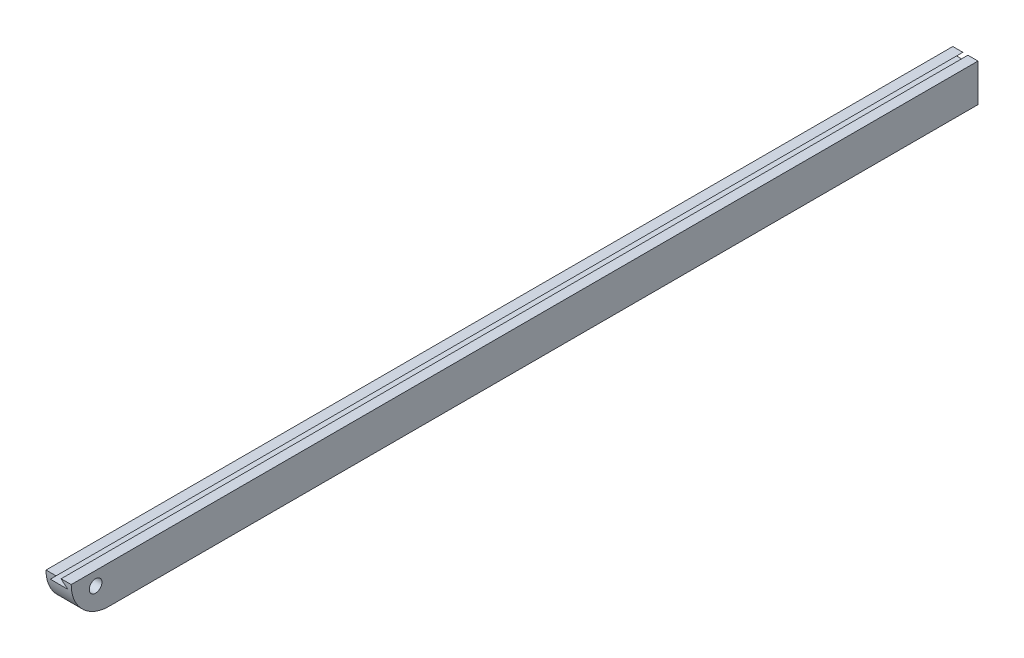
SolidWorks part; units mm, degrees
ref_plane "Front Plane" through (0, 0, 0) normal (0, 0, 1) x (1, 0, 0)
ref_plane "Top Plane" through (0, 0, 0) normal (0, 1, 0) x (1, 0, 0)
ref_plane "Right Plane" through (0, 0, 0) normal (1, 0, 0) x (0, 0, -1)
sketch "Sketch1" plane through (0, 0, 0) normal (0, 0, 1) x (1, 0, 0)
  line L0 (5.08, 0) -> (1.905, -3.175)
  line L1 (0, 0) -> (5.08, 0)
  line L2 (0, 0) -> (0, -19.05)
  line L3 (0, -19.05) -> (12.7, -19.05)
  line L4 (12.7, 0) -> (12.7, -19.05)
  line L5 (1.905, -3.175) -> (10.795, -3.175)
  line L6 (10.795, -3.175) -> (7.62, 0)
  line L7 (7.62, 0) -> (12.7, 0)
  dimension "D1" = 12.7
  dimension "D2" = 19.05
  dimension "D3" = 3.175
  dimension "D4" = 45
  dimension "D5" = 45
  dimension "D6" = 8.89
  dimension "D7" = 1.905
extrude "Boss-Extrude1" add sketch "Sketch1" along normal blind 457.2
sketch "Sketch2" plane through (12.7, 0, 0) normal (1, 0, 0) x (0, 0, -1)
  line L0 (-457.2, 0) -> (0, 0) construction
  line L1 (-457.2, -19.05) -> (-457.2, 0) construction
  line L2 (-457.2, -19.05) -> (0, -19.05) construction
  line L3 (-457.2, 0) -> (-457.2, -19.05)
  line L4 (-457.2, -19.05) -> (-438.15, -19.05)
  arc A0 (-457.2, 0) -> (-438.15, -19.05) centre (-438.15, 0) ccw
extrude "Cut-Extrude1" cut sketch "Sketch2" against normal through all
sketch "Sketch3" plane through (12.7, 0, 0) normal (1, 0, 0) x (0, 0, -1)
  line L0 (-451.6204, -13.4704) -> (-438.15, 0) construction
  circle A0 centre (-444.8852, -6.7352) radius 3.175
  arc A1 (-457.2, 0) -> (-438.15, -19.05) centre (-438.15, 0) ccw construction
  point P8 (-444.8852, -6.7352)
  dimension "D1" = 6.35
extrude "Cut-Extrude2" cut sketch "Sketch3" against normal through all
sketch "Sketch4" plane through (0, 0, 0) normal (0, 0, -1) x (-1, 0, 0)
  line L0 (0, -19.05) -> (-12.7, -19.05) construction
  line L1 (0, 0) -> (0, -19.05) construction
  circle A0 centre (-6.35, -11.43) radius 4.445
  point P2 (0, 0)
  dimension "D1" = 8.89
  dimension "D2" = 7.62
  dimension "D3" = 6.35
extrude "Cut-Extrude3" cut sketch "Sketch4" against normal blind 406.4
